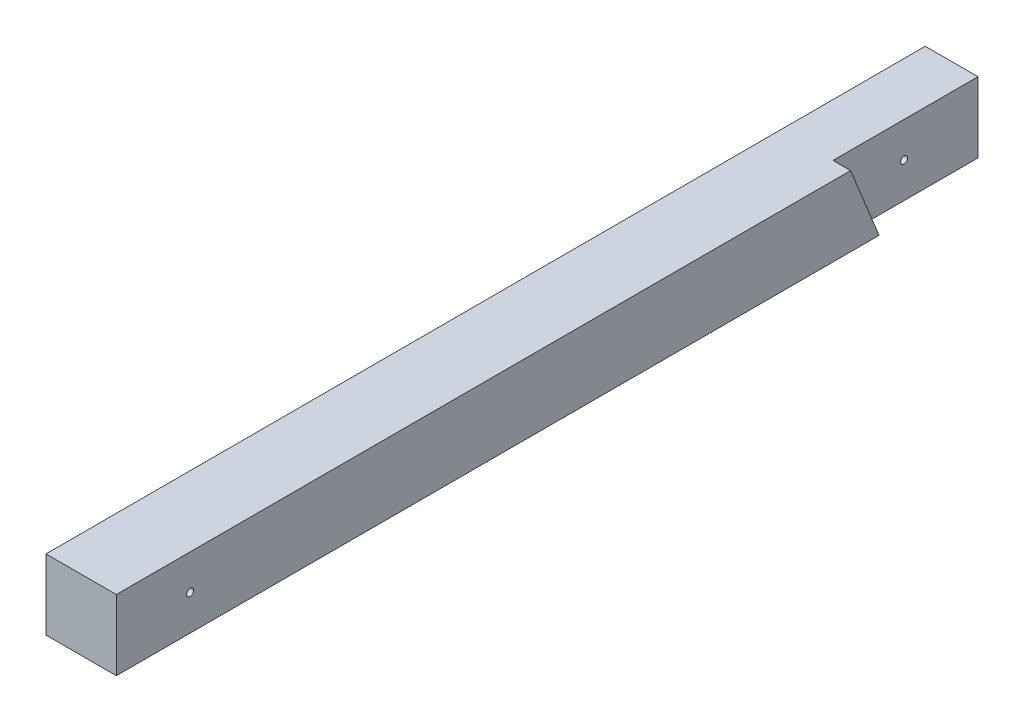
SolidWorks part; units mm, degrees
material "Pine"
ref_plane "Front Plane" through (0, 0, 0) normal (0, 0, 1) x (1, 0, 0)
ref_plane "Top Plane" through (0, 0, 0) normal (0, 1, 0) x (1, 0, 0)
ref_plane "Right Plane" through (0, 0, 0) normal (1, 0, 0) x (0, 0, -1)
sketch "Sketch1" plane through (0, 0, 0) normal (0, 0, 1) x (1, 0, 0)
  line L1 (-50, 50) -> (50, 50)
  line L2 (-50, 50) -> (-50, -50)
  line L3 (-50, -50) -> (50, -50)
  line L4 (50, 50) -> (50, -50)
  line L5 (-50, 50) -> (50, -50) construction
  line L6 (-50, -50) -> (50, 50) construction
  point P0 (0, 0)
  dimension "D1" = 100
  dimension "D2" = 100
extrude "Boss-Extrude1" add sketch "Sketch1" along normal mid plane 1250
sketch "Sketch2" plane through (-50, 0, 0) normal (-1, 0, 0) x (0, 0, 1)
  circle A0 centre (-520, 0) radius 5
  circle A1 centre (520, 0) radius 5
  dimension "D1" = 10
  dimension "D2" = 520
  dimension "D3" = 520
extrude "Cut-Extrude1" cut sketch "Sketch2" against normal through all
sketch "Sketch3" plane through (50, 0, 0) normal (1, 0, 0) x (0, 0, -1)
  line L0 (418.892, 50) -> (459.3158, -50)
  line L1 (-625, 50) -> (625, 50) construction
  line L2 (103.6858, 829.7541) -> (723.8141, -704.3132) construction
  line L3 (-625, -50) -> (625, -50) construction
  line L4 (459.3158, -50) -> (625, -50)
  line L5 (625, -50) -> (625, 50)
  line L6 (625, 50) -> (418.892, 50)
extrude "Cut-Extrude2" cut sketch "Sketch3" against normal blind 25
